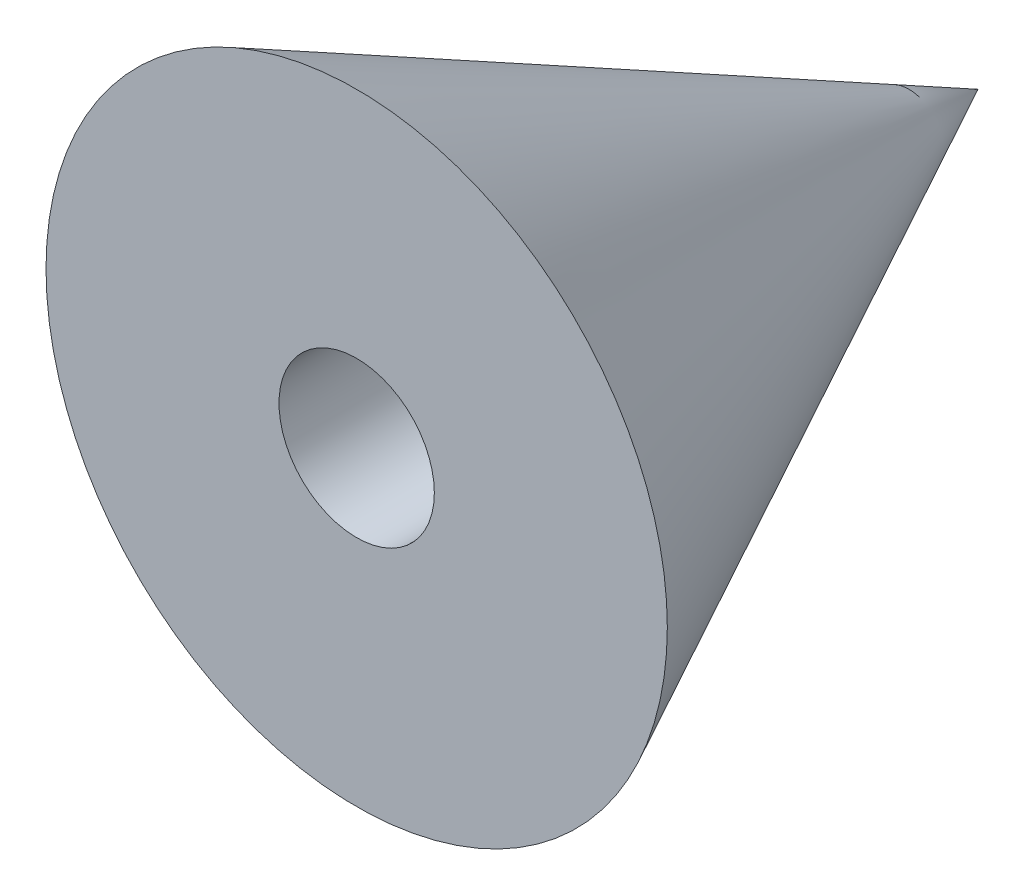
SolidWorks part; units mm, degrees
ref_plane "Front Plane" through (0, 0, 0) normal (0, 0, 1) x (1, 0, 0)
ref_plane "Top Plane" through (0, 0, 0) normal (0, 1, 0) x (1, 0, 0)
ref_plane "Right Plane" through (0, 0, 0) normal (1, 0, 0) x (0, 0, -1)
sketch "Sketch2" plane through (0, 0, 0) normal (0, 1, 0) x (1, 0, 0)
  line L0 (0, 0) -> (-10, 0)
  line L1 (-10, 0) -> (0, 20)
  line L2 (0, 20) -> (0, 0)
  dimension "D1" = 10
  dimension "D2" = 20
revolve "Revolve1" add sketch "Sketch2" angle 360 about L2
sketch "Sketch3" plane through (0, 0, 0) normal (0, 0, 1) x (1, 0, 0)
  circle A0 centre (0, 0) radius 2.5
  dimension "D1" = 5
extrude "Cut-Extrude2" cut sketch "Sketch3" against normal blind 5
